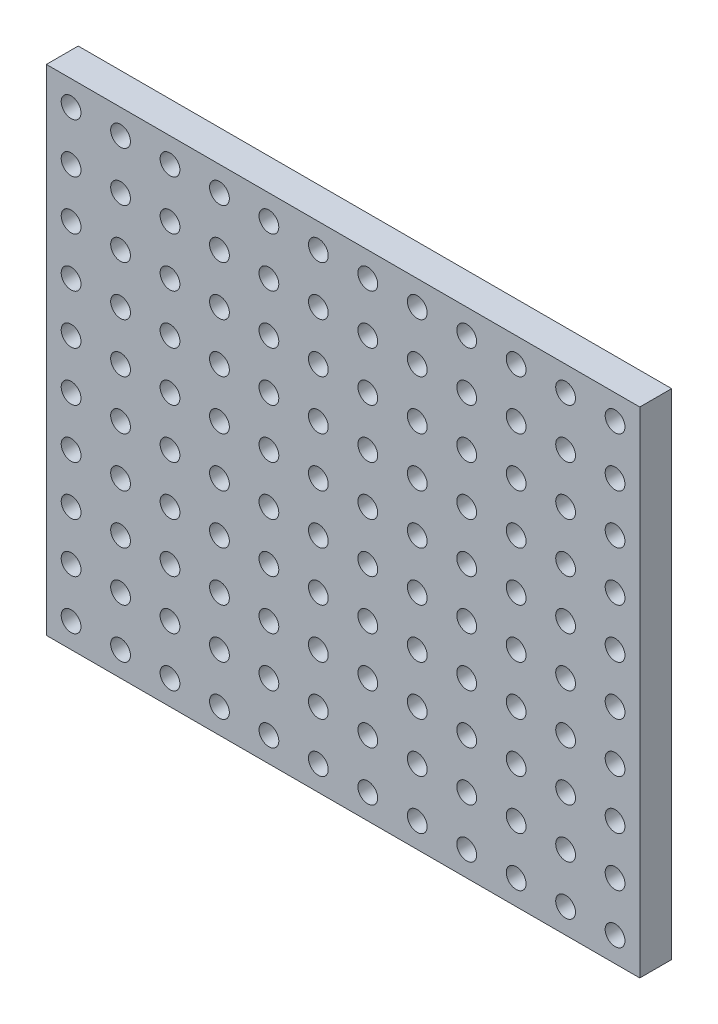
SolidWorks part; units mm, degrees
ref_plane "Front Plane" through (0, 0, 0) normal (0, 0, 1) x (1, 0, 0)
ref_plane "Top Plane" through (0, 0, 0) normal (0, 1, 0) x (1, 0, 0)
ref_plane "Right Plane" through (0, 0, 0) normal (1, 0, 0) x (0, 0, -1)
sketch "Sketch1" plane through (0, 0, 0) normal (0, 0, 1) x (1, 0, 0)
  line L0 (0, 12.5) -> (0, -12.5) construction
  line L1 (-15, 12.5) -> (15, 12.5)
  line L2 (-15, 12.5) -> (-15, -12.5)
  line L3 (-15, -12.5) -> (15, -12.5)
  line L4 (15, 12.5) -> (15, -12.5)
  line L5 (-15, 12.5) -> (15, -12.5) construction
  line L6 (-15, -12.5) -> (15, 12.5) construction
  line L7 (-13.75, -11.25) -> (-11.25, -11.25) construction
  line L8 (-13.75, -11.25) -> (-13.75, -8.75) construction
  circle A0 centre (-13.75, -11.25) radius 0.5
  circle A1 centre (-11.25, -11.25) radius 0.5
  circle A2 centre (-8.75, -11.25) radius 0.5
  circle A3 centre (-6.25, -11.25) radius 0.5
  circle A4 centre (-3.75, -11.25) radius 0.5
  circle A5 centre (-1.25, -11.25) radius 0.5
  circle A6 centre (1.25, -11.25) radius 0.5
  circle A7 centre (3.75, -11.25) radius 0.5
  circle A8 centre (6.25, -11.25) radius 0.5
  circle A9 centre (8.75, -11.25) radius 0.5
  circle A10 centre (11.25, -11.25) radius 0.5
  circle A11 centre (13.75, -11.25) radius 0.5
  circle A12 centre (-11.25, -8.75) radius 0.5
  circle A13 centre (-8.75, -8.75) radius 0.5
  circle A14 centre (-6.25, -8.75) radius 0.5
  circle A15 centre (-3.75, -8.75) radius 0.5
  circle A16 centre (-1.25, -8.75) radius 0.5
  circle A17 centre (1.25, -8.75) radius 0.5
  circle A18 centre (3.75, -8.75) radius 0.5
  circle A19 centre (6.25, -8.75) radius 0.5
  circle A20 centre (8.75, -8.75) radius 0.5
  circle A21 centre (11.25, -8.75) radius 0.5
  circle A22 centre (13.75, -8.75) radius 0.5
  circle A23 centre (-11.25, -6.25) radius 0.5
  circle A24 centre (-8.75, -6.25) radius 0.5
  circle A25 centre (-6.25, -6.25) radius 0.5
  circle A26 centre (-3.75, -6.25) radius 0.5
  circle A27 centre (-1.25, -6.25) radius 0.5
  circle A28 centre (1.25, -6.25) radius 0.5
  circle A29 centre (3.75, -6.25) radius 0.5
  circle A30 centre (6.25, -6.25) radius 0.5
  circle A31 centre (8.75, -6.25) radius 0.5
  circle A32 centre (11.25, -6.25) radius 0.5
  circle A33 centre (13.75, -6.25) radius 0.5
  circle A34 centre (-11.25, -3.75) radius 0.5
  circle A35 centre (-8.75, -3.75) radius 0.5
  circle A36 centre (-6.25, -3.75) radius 0.5
  circle A37 centre (-3.75, -3.75) radius 0.5
  circle A38 centre (-1.25, -3.75) radius 0.5
  circle A39 centre (1.25, -3.75) radius 0.5
  circle A40 centre (3.75, -3.75) radius 0.5
  circle A41 centre (6.25, -3.75) radius 0.5
  circle A42 centre (8.75, -3.75) radius 0.5
  circle A43 centre (11.25, -3.75) radius 0.5
  circle A44 centre (13.75, -3.75) radius 0.5
  circle A45 centre (-11.25, -1.25) radius 0.5
  circle A46 centre (-8.75, -1.25) radius 0.5
  circle A47 centre (-6.25, -1.25) radius 0.5
  circle A48 centre (-3.75, -1.25) radius 0.5
  circle A49 centre (-1.25, -1.25) radius 0.5
  circle A50 centre (1.25, -1.25) radius 0.5
  circle A51 centre (3.75, -1.25) radius 0.5
  circle A52 centre (6.25, -1.25) radius 0.5
  circle A53 centre (8.75, -1.25) radius 0.5
  circle A54 centre (11.25, -1.25) radius 0.5
  circle A55 centre (13.75, -1.25) radius 0.5
  circle A56 centre (-11.25, 1.25) radius 0.5
  circle A57 centre (-8.75, 1.25) radius 0.5
  circle A58 centre (-6.25, 1.25) radius 0.5
  circle A59 centre (-3.75, 1.25) radius 0.5
  circle A60 centre (-1.25, 1.25) radius 0.5
  circle A61 centre (1.25, 1.25) radius 0.5
  circle A62 centre (3.75, 1.25) radius 0.5
  circle A63 centre (6.25, 1.25) radius 0.5
  circle A64 centre (8.75, 1.25) radius 0.5
  circle A65 centre (11.25, 1.25) radius 0.5
  circle A66 centre (13.75, 1.25) radius 0.5
  circle A67 centre (-11.25, 3.75) radius 0.5
  circle A68 centre (-8.75, 3.75) radius 0.5
  circle A69 centre (-6.25, 3.75) radius 0.5
  circle A70 centre (-3.75, 3.75) radius 0.5
  circle A71 centre (-1.25, 3.75) radius 0.5
  circle A72 centre (1.25, 3.75) radius 0.5
  circle A73 centre (3.75, 3.75) radius 0.5
  circle A74 centre (6.25, 3.75) radius 0.5
  circle A75 centre (8.75, 3.75) radius 0.5
  circle A76 centre (11.25, 3.75) radius 0.5
  circle A77 centre (13.75, 3.75) radius 0.5
  circle A78 centre (-11.25, 6.25) radius 0.5
  circle A79 centre (-8.75, 6.25) radius 0.5
  circle A80 centre (-6.25, 6.25) radius 0.5
  circle A81 centre (-3.75, 6.25) radius 0.5
  circle A82 centre (-1.25, 6.25) radius 0.5
  circle A83 centre (1.25, 6.25) radius 0.5
  circle A84 centre (3.75, 6.25) radius 0.5
  circle A85 centre (6.25, 6.25) radius 0.5
  circle A86 centre (8.75, 6.25) radius 0.5
  circle A87 centre (11.25, 6.25) radius 0.5
  circle A88 centre (13.75, 6.25) radius 0.5
  circle A89 centre (-11.25, 8.75) radius 0.5
  circle A90 centre (-8.75, 8.75) radius 0.5
  circle A91 centre (-6.25, 8.75) radius 0.5
  circle A92 centre (-3.75, 8.75) radius 0.5
  circle A93 centre (-1.25, 8.75) radius 0.5
  circle A94 centre (1.25, 8.75) radius 0.5
  circle A95 centre (3.75, 8.75) radius 0.5
  circle A96 centre (6.25, 8.75) radius 0.5
  circle A97 centre (8.75, 8.75) radius 0.5
  circle A98 centre (11.25, 8.75) radius 0.5
  circle A99 centre (13.75, 8.75) radius 0.5
  circle A100 centre (-11.25, 11.25) radius 0.5
  circle A101 centre (-8.75, 11.25) radius 0.5
  circle A102 centre (-6.25, 11.25) radius 0.5
  circle A103 centre (-3.75, 11.25) radius 0.5
  circle A104 centre (-1.25, 11.25) radius 0.5
  circle A105 centre (1.25, 11.25) radius 0.5
  circle A106 centre (3.75, 11.25) radius 0.5
  circle A107 centre (6.25, 11.25) radius 0.5
  circle A108 centre (8.75, 11.25) radius 0.5
  circle A109 centre (11.25, 11.25) radius 0.5
  circle A110 centre (13.75, 11.25) radius 0.5
  circle A111 centre (-13.75, -8.75) radius 0.5
  circle A112 centre (-13.75, -6.25) radius 0.5
  circle A113 centre (-13.75, -3.75) radius 0.5
  circle A114 centre (-13.75, -1.25) radius 0.5
  circle A115 centre (-13.75, 1.25) radius 0.5
  circle A116 centre (-13.75, 3.75) radius 0.5
  circle A117 centre (-13.75, 6.25) radius 0.5
  circle A118 centre (-13.75, 8.75) radius 0.5
  circle A119 centre (-13.75, 11.25) radius 0.5
  point P0 (0, 0)
  dimension "D3" = 1
  dimension "D4" = 1.25
  dimension "D5" = 1.25
  dimension "D7" = 10
  dimension "D1" = 25
  dimension "D2" = 30
  dimension "D8" = 90
  dimension "D9" = 2.5
  dimension "D10" = 2.5
  dimension "D6" = 12
extrude "Boss-Extrude1" add sketch "Sketch1" along normal blind 1.61
